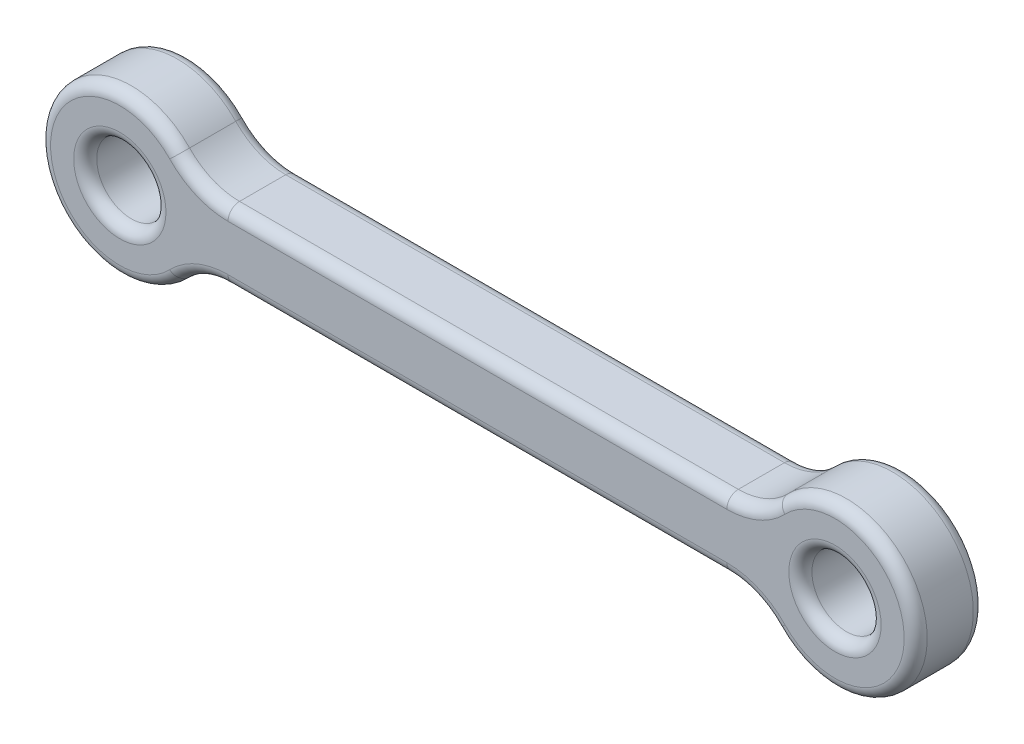
SolidWorks part; units mm, degrees
ref_plane "Front Plane" through (0, 0, 0) normal (0, 0, 1) x (1, 0, 0)
ref_plane "Top Plane" through (0, 0, 0) normal (0, 1, 0) x (1, 0, 0)
ref_plane "Right Plane" through (0, 0, 0) normal (1, 0, 0) x (0, 0, -1)
sketch "Sketch1" plane through (0, 0, 0) normal (0, 0, 1) x (1, 0, 0)
  line L0 (0, 14.0682) -> (0, -13.1713) construction
  line L1 (-12.5727, 0) -> (34.5, 0) construction
  line L2 (4.6904, 1.5) -> (26.3096, 1.5)
  line L3 (4.6904, -1.5) -> (26.3096, -1.5)
  line L4 (16.2641, 6.677) -> (16.2641, -8.0775) construction
  circle A0 centre (0, 0) radius 1.5
  arc A1 (2.5256, 2.4231) -> (2.5256, -2.4231) centre (0, 0) ccw
  circle A2 centre (31, 0) radius 1.5
  arc A4 (2.5256, 2.4231) -> (4.6904, 1.5) centre (4.6904, 4.5) ccw
  arc A5 (2.5256, -2.4231) -> (4.6904, -1.5) centre (4.6904, -4.5) cw
  arc A6 (26.3096, 1.5) -> (28.4744, 2.4231) centre (26.3096, 4.5) ccw
  arc A7 (26.3096, -1.5) -> (28.4744, -2.4231) centre (26.3096, -4.5) cw
  arc A8 (28.4744, -2.4231) -> (28.4744, 2.4231) centre (31, 0) ccw
  dimension "D1" = 31
  dimension "D2" = 7
  dimension "D3" = 3
  dimension "D5" = 6
  dimension "D6" = 6
  dimension "D4" = 1.5
extrude "Boss-Extrude1" add sketch "Sketch1" against normal blind 3
fillet "Fillet1" radius 0.5 19 edges at (27.4863, 1.7404, -3) (34.5, 0, -3) (27.4863, -1.7404, -3) (15.5, -1.5, -3) (3.5137, -1.7404, -3) (-3.5, 0, -3) (3.5137, 1.7404, -3) (27.4863, 1.7404, 0) (34.5, 0, 0) (27.4863, -1.7404, 0) (15.5, -1.5, 0) (3.5137, -1.7404, 0) (-3.5, 0, 0) (3.5137, 1.7404, 0) (1.5, 0, 0) (32.5, 0, -3) (32.5, 0, 0) (15.5, 1.5, -3) (15.5, 1.5, 0)
scale "Scale1" scale about centroid uniform scaling yes scale factor 1.9
